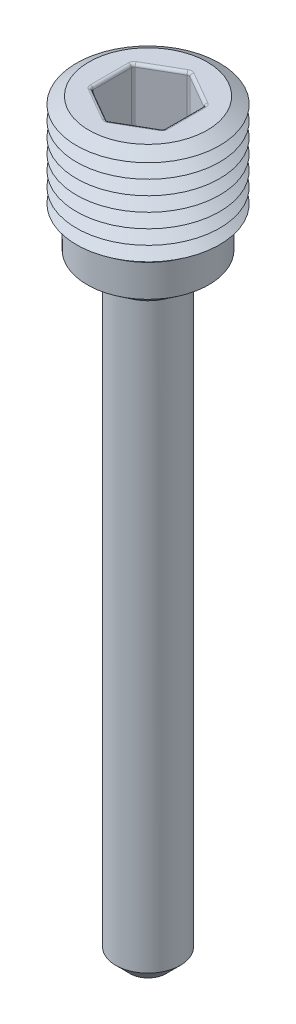
SolidWorks part; units mm, degrees
ref_plane "Front Plane" through (0, 0, 0) normal (0, 0, 1) x (1, 0, 0)
ref_plane "Top Plane" through (0, 0, 0) normal (0, 1, 0) x (1, 0, 0)
ref_plane "Right Plane" through (0, 0, 0) normal (1, 0, 0) x (0, 0, -1)
sketch "Sketch1" plane through (0, 0, 0) normal (0, 0, 1) x (1, 0, 0)
  line L0 (0, 0) -> (-2.25, 0)
  line L1 (-2.25, 0) -> (-2.25, 41.7)
  line L2 (-2.25, 41.7) -> (-4.25, 43.2)
  line L3 (-4.25, 43.2) -> (-4.25, 45.5)
  line L4 (-4.25, 45.5) -> (-5, 45.5)
  line L5 (-5, 45.5) -> (-5, 52.5)
  line L6 (-5, 52.5) -> (0, 52.5)
  line L7 (0, 52.5) -> (0, 0)
  dimension "D1" = 2.25
  dimension "D2" = 41.7
  dimension "D3" = 4.25
  dimension "D4" = 1.5
  dimension "D5" = 5
  dimension "D6" = 7
  dimension "D7" = 52.5
revolve "Revolve1" add sketch "Sketch1" angle 360 about L7
chamfer "Chamfer1" distance 1 angle 45 1 edges at (-2.25, 0, 0)
chamfer "Chamfer2" distance 0.5 angle 45 1 edges at (-5, 52.5, 0)
sketch "Sketch2" plane through (0, 52.5, 0) normal (0, 1, 0) x (1, 0, 0)
  line L1 (0, -2.8868) -> (2.5, -1.4434)
  line L2 (2.5, -1.4434) -> (2.5, 1.4434)
  line L3 (2.5, 1.4434) -> (0, 2.8868)
  line L4 (0, 2.8868) -> (-2.5, 1.4434)
  line L5 (-2.5, 1.4434) -> (-2.5, -1.4434)
  line L6 (-2.5, -1.4434) -> (0, -2.8868)
  circle A0 centre (0, 0) radius 2.5 construction
  dimension "D1" = 5
extrude "Cut-Extrude1" cut sketch "Sketch2" against normal blind 7
fillet "Fillet1" radius 0.2 18 edges at (2.5, 52.5, 0) (2.5, 49, 1.4434) (1.25, 52.5, 2.1651) (0, 49, 2.8868) (-1.25, 52.5, 2.1651) (-2.5, 49, 1.4434) (-2.5, 52.5, 0) (-2.5, 45.5, 0) (2.5, 45.5, 0) (1.25, 45.5, 2.1651) (-1.25, 45.5, 2.1651) (-1.25, 45.5, -2.1651) (-2.5, 49, -1.4434) (-1.25, 52.5, -2.1651) (2.5, 49, -1.4434) (1.25, 45.5, -2.1651) (0, 49, -2.8868) (1.25, 52.5, -2.1651)
sketch "Sketch3" plane through (0, 0, 0) normal (0, 0, 1) x (1, 0, 0)
  line L0 (0, 53.5473) -> (0, 54.5997) construction
  line L1 (5, 52) -> (5, 53)
  line L2 (5, 53) -> (4.134, 52.5)
  line L3 (4.134, 52.5) -> (5, 52)
  line L4 (5, 52) -> (4.134, 51.5)
  line L5 (5, 51) -> (5, 52)
  line L6 (4.134, 51.5) -> (5, 51)
  line L7 (5, 51) -> (4.134, 50.5)
  line L8 (5, 50) -> (5, 51)
  line L9 (4.134, 50.5) -> (5, 50)
  line L10 (5, 50) -> (4.134, 49.5)
  line L11 (5, 49) -> (5, 50)
  line L12 (4.134, 49.5) -> (5, 49)
  line L13 (5, 49) -> (4.134, 48.5)
  line L14 (5, 48) -> (5, 49)
  line L15 (4.134, 48.5) -> (5, 48)
  line L16 (5, 48) -> (4.134, 47.5)
  line L17 (5, 47) -> (5, 48)
  line L18 (4.134, 47.5) -> (5, 47)
  line L19 (5, 47) -> (4.134, 46.5)
  line L20 (5, 46) -> (5, 47)
  line L21 (4.134, 46.5) -> (5, 46)
  line L22 (5, 46) -> (4.134, 45.5)
  line L23 (5, 45) -> (5, 46)
  line L24 (4.134, 45.5) -> (5, 45)
  dimension "D1" = 1
  dimension "D2" = 8
revolve "Cut-Revolve1" cut sketch "Sketch3" angle 360 about L0
